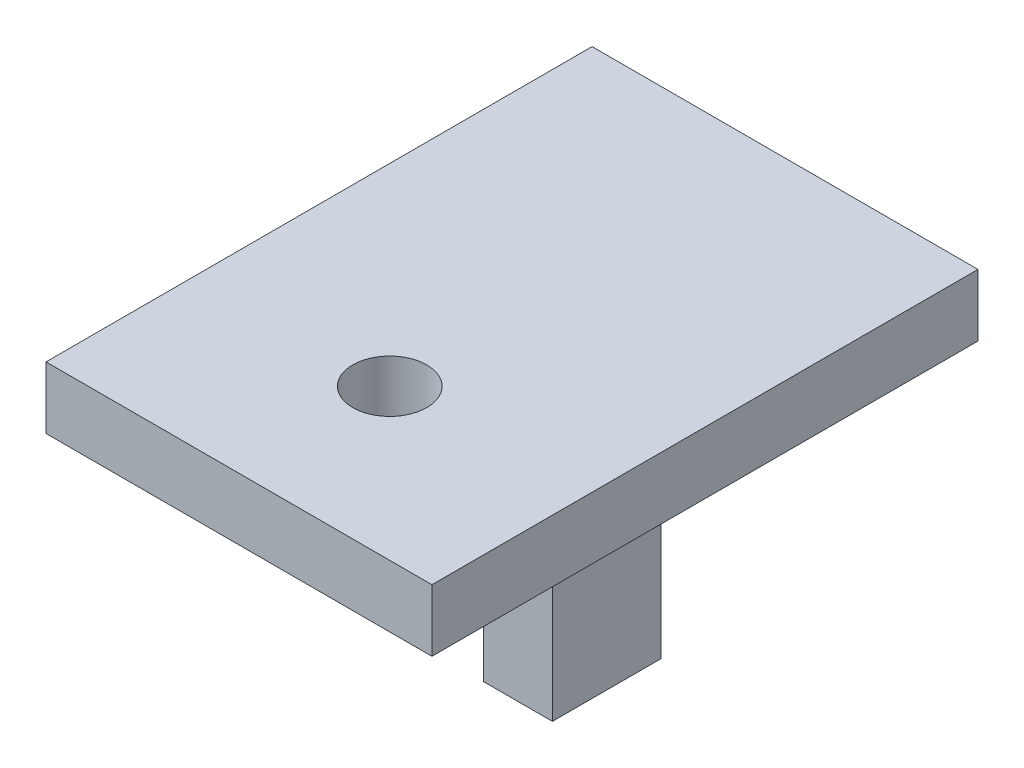
SolidWorks part; units mm, degrees
ref_plane "Front Plane" through (0, 0, 0) normal (0, 0, 1) x (1, 0, 0)
ref_plane "Top Plane" through (0, 0, 0) normal (0, 1, 0) x (1, 0, 0)
ref_plane "Right Plane" through (0, 0, 0) normal (1, 0, 0) x (0, 0, -1)
sketch "Sketch1" plane through (0, 0, 0) normal (0, 1, 0) x (1, 0, 0)
  line L1 (-31.1, 40.4921) -> (31.1, 40.4921)
  line L2 (-31.1, 40.4921) -> (-31.1, -47.5179)
  line L3 (-31.1, -47.5179) -> (31.1, -47.5179)
  line L4 (31.1, 40.4921) -> (31.1, -47.5179)
  point P0 (0, 0)
  dimension "D1" = 62.2
  dimension "D2" = 88.01
extrude "Boss-Extrude1" add sketch "Sketch1" along normal blind 10
sketch "Sketch2" plane through (0, 10, 0) normal (0, 1, 0) x (1, 0, 0)
  line L0 (-31.1, -47.5179) -> (31.1, -47.5179) construction
  circle A0 centre (0, -23.2179) radius 5.969
  dimension "D1" = 24.3
extrude "Cut-Extrude1" cut sketch "Sketch2" against normal blind 10
sketch "Sketch3" plane through (0, 0, 0) normal (0, -1, 0) x (1, 0, 0)
  line L0 (31.1, -40.4921) -> (-31.1, -40.4921) construction
  line L1 (-20.01, -40.4921) -> (-31.1, -40.4921)
  line L2 (-20.01, -40.4921) -> (-20.01, -23.0094)
  line L3 (-20.01, -23.0094) -> (-31.1, -23.0094)
  line L4 (-31.1, -40.4921) -> (-31.1, -23.0094)
  line L5 (-31.1, -40.4921) -> (-31.1, 47.5179) construction
  dimension "D1" = 11.09
  dimension "D2" = 0
  dimension "D3" = 17.4826
  dimension "D4" = 0
extrude "Boss-Extrude2" add sketch "Sketch3" along normal blind 69.9
sketch "Sketch5" plane through (0, 0, 0) normal (0, -1, 0) x (-1, 0, 0)
  circle A0 centre (0, -23.2179) radius 50
sketch "Sketch14" plane through (0, 0, 0) normal (0, -1, 0) x (1, 0, 0)
  line L0 (-25.9067, -23.0083) -> (-20.0067, -23.0092) construction
  line L1 (-20.0067, -23.0092) -> (-20.0049, -10.1092) construction
  line L2 (-25.9067, -23.0083) -> (-20.0067, -23.0092)
  line L3 (-20.0067, -23.0092) -> (-20.0049, -10.1092)
